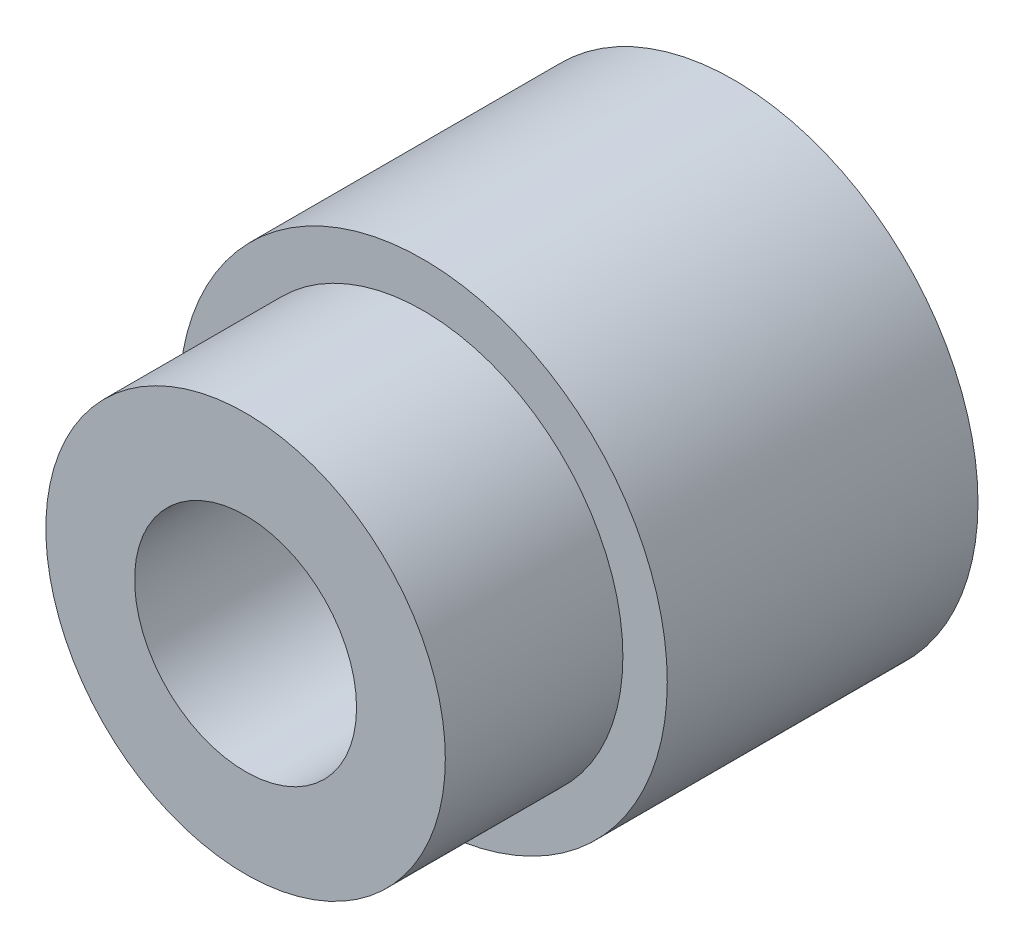
SolidWorks part; units mm, degrees
ref_plane "Front Plane" through (0, 0, 0) normal (0, 0, 1) x (1, 0, 0)
ref_plane "Top Plane" through (0, 0, 0) normal (0, 1, 0) x (1, 0, 0)
ref_plane "Right Plane" through (0, 0, 0) normal (1, 0, 0) x (0, 0, -1)
sketch "Sketch1" plane through (0, 0, 0) normal (0, 0, 1) x (1, 0, 0)
  circle A0 centre (0, 0) radius 5.5
  dimension "D1" = 11
extrude "Boss-Extrude1" add sketch "Sketch1" along normal blind 7
sketch "Sketch2" plane through (0, 0, 7) normal (0, 0, 1) x (1, 0, 0)
  circle A0 centre (0, 0) radius 4.5
  dimension "D1" = 9
extrude "Boss-Extrude2" add sketch "Sketch2" along normal blind 4
sketch "Sketch3" plane through (0, 0, 11) normal (0, 0, 1) x (1, 0, 0)
  circle A0 centre (0, 0) radius 2.5
  dimension "D1" = 5
extrude "Cut-Extrude1" cut sketch "Sketch3" against normal up to next
